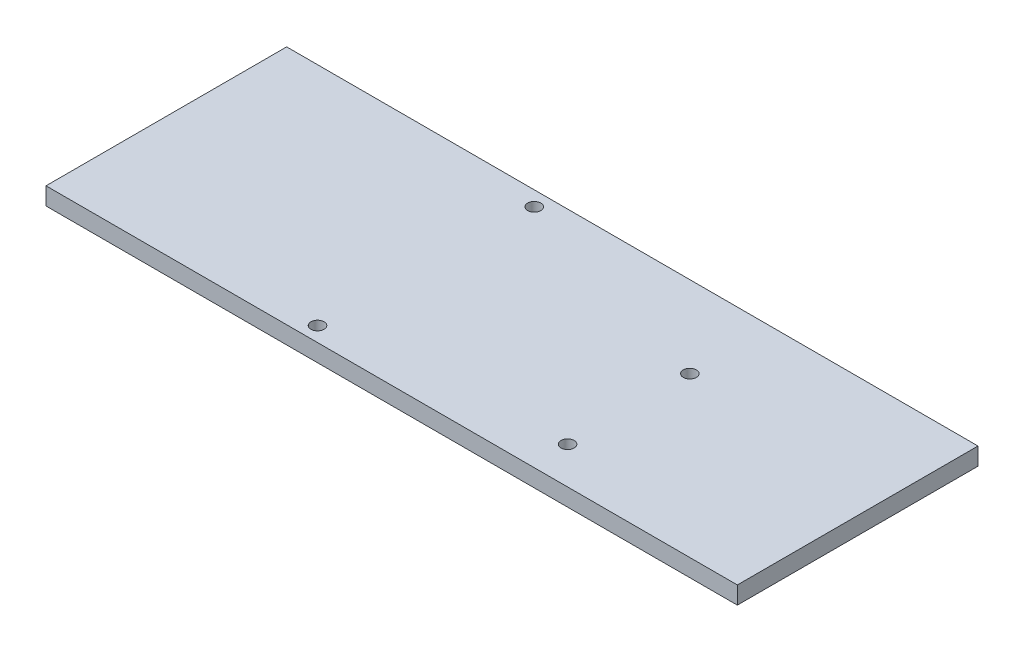
SolidWorks part; units mm, degrees
ref_plane "Front Plane" through (0, 0, 0) normal (0, 0, 1) x (1, 0, 0)
ref_plane "Top Plane" through (0, 0, 0) normal (0, 1, 0) x (1, 0, 0)
ref_plane "Right Plane" through (0, 0, 0) normal (1, 0, 0) x (0, 0, -1)
sketch "Sketch1" plane through (0, 0, 0) normal (0, 1, 0) x (1, 0, 0)
  line L1 (0, 0) -> (158, 0)
  line L2 (0, 0) -> (0, 55)
  line L3 (0, 55) -> (158, 55)
  line L4 (158, 0) -> (158, 55)
  dimension "D1" = 55
  dimension "D2" = 158
extrude "Boss-Extrude1" add sketch "Sketch1" along normal blind 4
ref_plane "Plane1" through (79, 0, 0) normal (1, 0, 0) x (0, 0, -1)
ref_plane "Plane2" through (0, 0, -27.5) normal (0, 0, 1) x (1, 0, 0)
sketch "Sketch2" plane through (0, 4, 0) normal (0, 1, 0) x (1, 0, 0)
  line L1 (158, 55) -> (0, 55) construction
  line L2 (0, 0) -> (158, 0) construction
  line L4 (158, 0) -> (158, 55) construction
  line L5 (158, 55) -> (158, 0) construction
  circle A0 centre (110.75, 8.45) radius 1.5
  circle A2 centre (110.75, 36.39) radius 1.5
  circle A4 centre (58.68, 3.37) radius 1.5
  circle A6 centre (59.95, 51.63) radius 1.5
  point P0 (55.1485, 66.5)
  point P1 (110.75, 36.39)
  point P2 (110.75, 8.45)
  point P3 (58.68, 3.37)
  point P6 (59.95, 51.63)
  dimension "D1" = 3.37
  dimension "D2" = 3.37
  dimension "D3" = 8.45
  dimension "D4" = 18.61
  dimension "D5" = 47.25
  dimension "D6" = 47.25
  dimension "D7" = 99.32
  dimension "D8" = 98.05
extrude "Cut-Extrude2" cut sketch "Sketch2" against normal up to next contours A2 | A6 | A0 | A4
